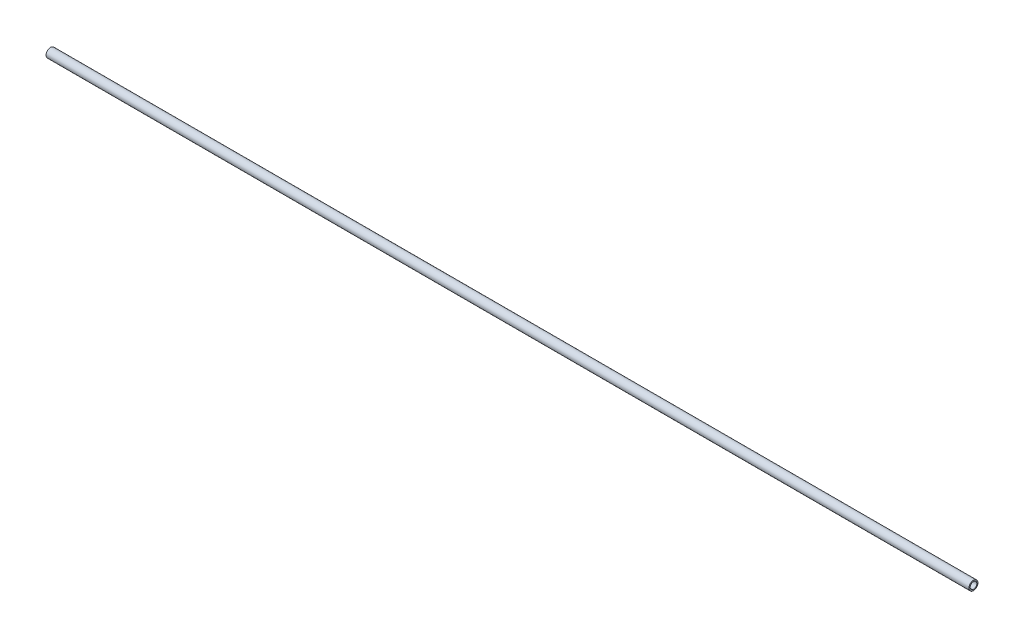
SolidWorks part; units mm, degrees
ref_plane "Front Plane" through (0, 0, 0) normal (0, 0, 1) x (1, 0, 0)
ref_plane "Top Plane" through (0, 0, 0) normal (0, 1, 0) x (1, 0, 0)
ref_plane "Right Plane" through (0, 0, 0) normal (1, 0, 0) x (0, 0, -1)
sketch "Sketch1" plane through (0, 0, 0) normal (1, 0, 0) x (0, 0, -1)
  circle A0 centre (0, 0) radius 4.7625
  circle A1 centre (0, 0) radius 3.5179
  dimension "D1" = 1.2446
extrude "Boss-Extrude1" add sketch "Sketch1" along normal blind 974.852
